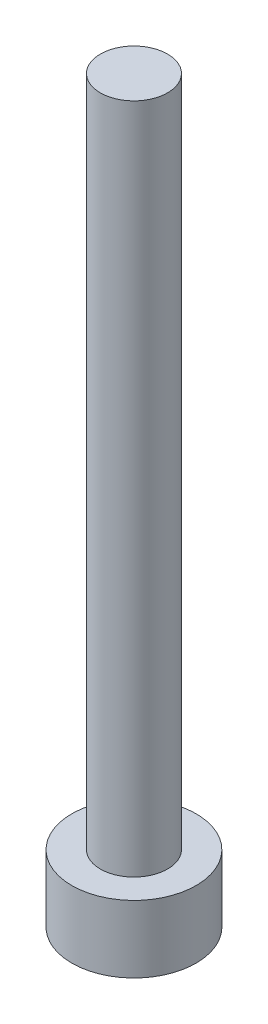
SolidWorks part; units mm, degrees
ref_plane "Front Plane" through (0, 0, 0) normal (0, 0, 1) x (1, 0, 0)
ref_plane "Top Plane" through (0, 0, 0) normal (0, 1, 0) x (1, 0, 0)
ref_plane "Right Plane" through (0, 0, 0) normal (1, 0, 0) x (0, 0, -1)
sketch "Sketch1" plane through (0, 0, 0) normal (0, 1, 0) x (1, 0, 0)
  circle A0 centre (0, 0) radius 1.85
  dimension "D1" = 3.7
extrude "Boss-Extrude1" add sketch "Sketch1" along normal blind 2
sketch "Sketch2" plane through (0, 2, 0) normal (0, 1, 0) x (1, 0, 0)
  circle A0 centre (0, 0) radius 1
  dimension "D1" = 2
extrude "Boss-Extrude2" add sketch "Sketch2" along normal blind 20
